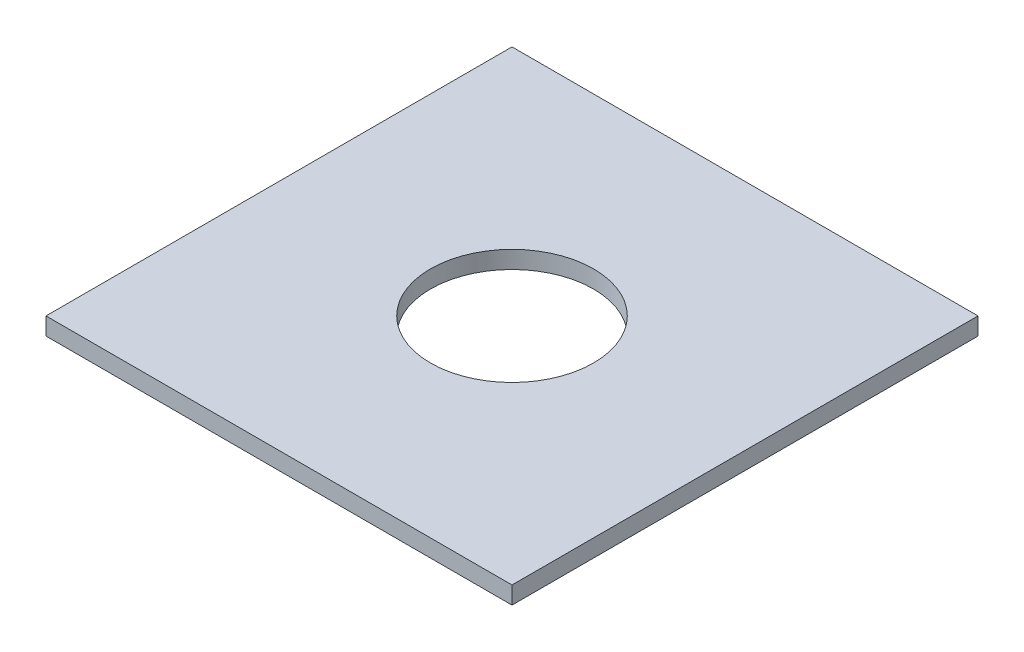
SolidWorks part; units mm, degrees
ref_plane "前视基准面" through (0, 0, 0) normal (0, 0, 1) x (1, 0, 0)
ref_plane "上视基准面" through (0, 0, 0) normal (0, 1, 0) x (1, 0, 0)
ref_plane "右视基准面" through (0, 0, 0) normal (1, 0, 0) x (0, 0, -1)
other "Configuration Table"
sketch "草图1" plane through (0, 0, 0) normal (0, 1, 0) x (1, 0, 0)
  line L1 (-40, -40) -> (40, -40)
  line L2 (-40, -40) -> (-40, 40)
  line L3 (-40, 40) -> (40, 40)
  line L4 (40, -40) -> (40, 40)
  line L5 (-40, -40) -> (40, 40) construction
  line L6 (-40, 40) -> (40, -40) construction
  circle A0 centre (0, 0) radius 16 construction
  circle A1 centre (0, 0) radius 14
  dimension "D1" = 28
  dimension "D2" = 32
  dimension "D3" = 80
extrude "凸台-拉伸1" add sketch "草图1" along normal blind 3
